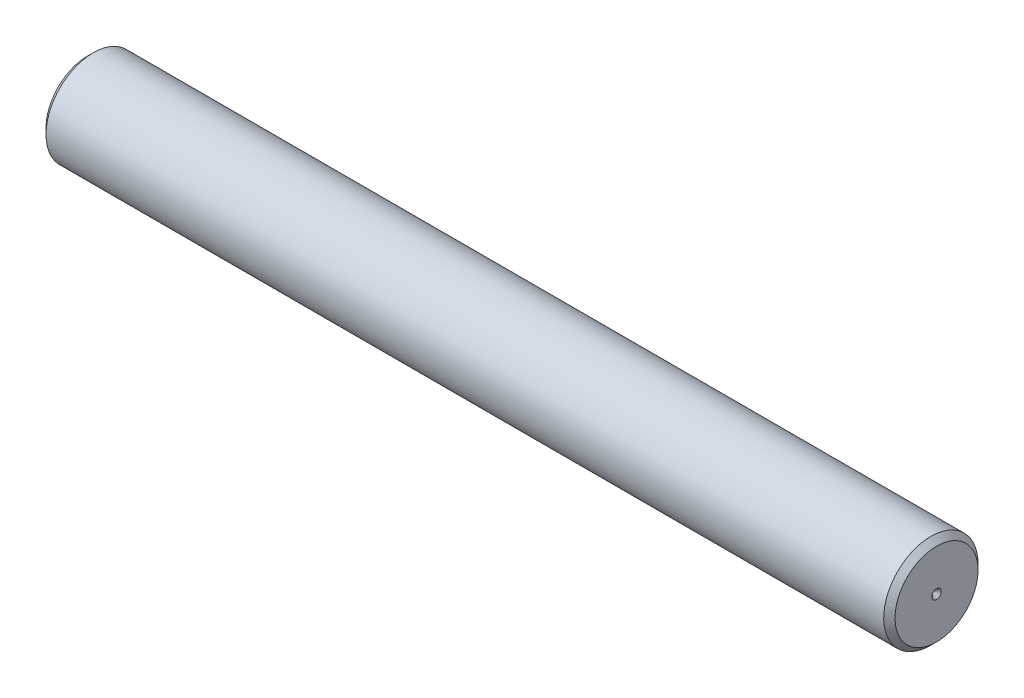
SolidWorks part; units mm, degrees
ref_plane "Front Plane" through (0, 0, 0) normal (0, 0, 1) x (1, 0, 0)
ref_plane "Top Plane" through (0, 0, 0) normal (0, 1, 0) x (1, 0, 0)
ref_plane "Right Plane" through (0, 0, 0) normal (1, 0, 0) x (0, 0, -1)
sketch "Sketch1" plane through (0, 0, 0) normal (0, 0, 1) x (1, 0, 0)
  line L0 (0, 0) -> (-45, 0) construction
  line L1 (0, 0) -> (0, 2.5)
  line L3 (0, 2.5) -> (-45, 2.5)
  line L5 (-45, 2.5) -> (-45, 0)
  line L6 (-45, 0) -> (0, 0)
  dimension "L" = 45
  dimension "D" = 5
revolve "Revolve1" add sketch "Sketch1" about L0
chamfer "Chamfer1" distance 0.3 2 edges at (0, 2.5, 0) (-45, 2.5, 0)
sketch "Sketch2" plane through (0, 0, 0) normal (0, 0, 1) x (1, 0, 0)
  line L0 (0, 0) -> (-45, 0) construction
  line L1 (-45, 0) -> (-44.75, 0)
  line L2 (-44.75, 0) -> (-45, 0.25)
  line L3 (-45, 0.25) -> (-45, 0)
  line L4 (0, 0) -> (0, 0.25)
  line L5 (0, 0.25) -> (-0.25, 0)
  line L6 (-0.25, 0) -> (0, 0)
  line L7 (-0.25, 0) -> (0, -0.25) construction
  line L8 (-44.75, 0) -> (-45, -0.25) construction
  dimension "KSS_1" = 0.5
  dimension "L" = 45
revolve "Cut-Revolve1" cut sketch "Sketch2" about L0
equation "\"KSS_1@Sketch2\"= \"D@Sketch1\" * 0.1"
equation "\"ANGLE360\"= 360"
